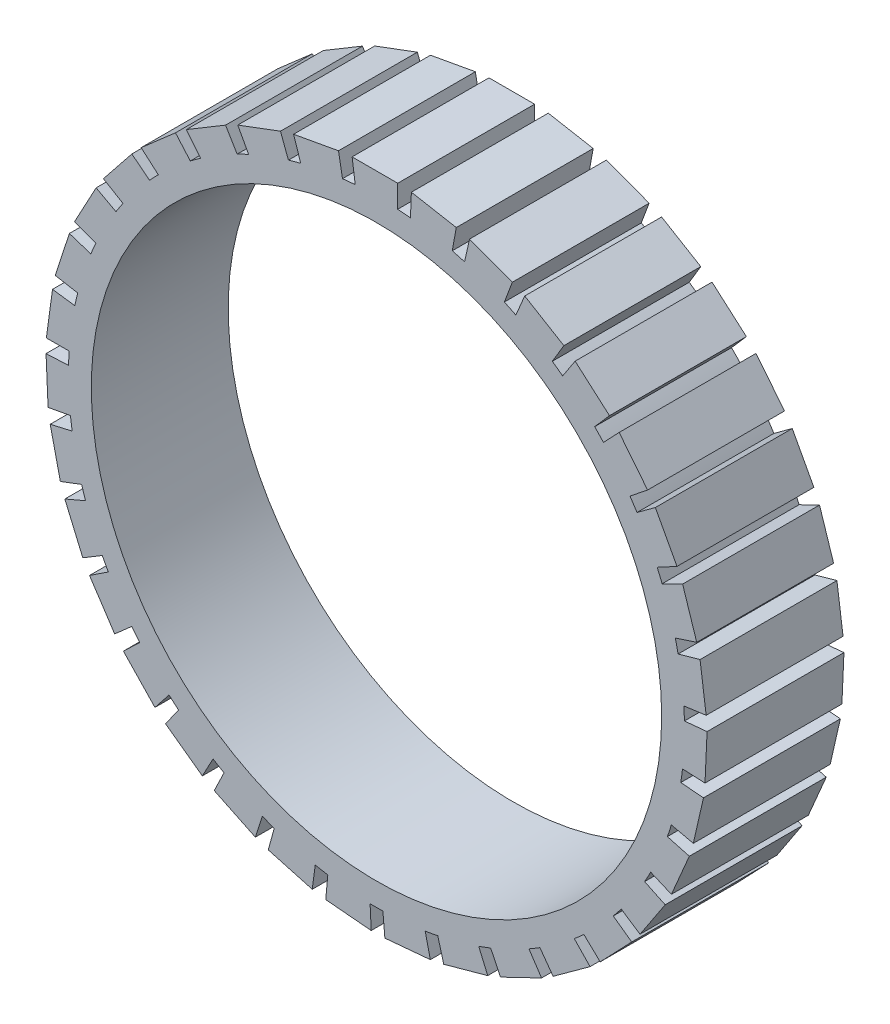
SolidWorks part; units mm, degrees
material "Rubber"
ref_plane "Front Plane" through (0, 0, 0) normal (0, 0, 1) x (1, 0, 0)
ref_plane "Top Plane" through (0, 0, 0) normal (0, 1, 0) x (1, 0, 0)
ref_plane "Right Plane" through (0, 0, 0) normal (1, 0, 0) x (0, 0, -1)
sketch "Sketch2" plane through (0, 0, 0) normal (0, 0, 1) x (1, 0, 0)
  line L1 (-2.1379, 28.9118) -> (1.8621, 28.9118)
  line L2 (-2.1379, 28.9118) -> (-1.8621, 26.9357)
  line L3 (1.8621, 28.9118) -> (1.8621, 26.9357)
  line L4 (3.0588, 28.8289) -> (6.9945, 28.1147)
  line L5 (3.0588, 28.8289) -> (2.9774, 26.8353)
  line L6 (6.9945, 28.1147) -> (6.6417, 26.1704)
  line L8 (8.1573, 27.8194) -> (11.9022, 26.4139)
  line L9 (8.1573, 27.8194) -> (7.7212, 25.8724)
  line L10 (11.9022, 26.4139) -> (11.2079, 24.5639)
  line L12 (12.9935, 25.9158) -> (16.4273, 23.8642)
  line L13 (12.9935, 25.9158) -> (12.2168, 24.078)
  line L14 (16.4273, 23.8642) -> (15.4138, 22.1679)
  line L16 (17.4122, 23.1793) -> (20.4245, 20.5475)
  line L17 (17.4122, 23.1793) -> (16.3198, 21.5096)
  line L18 (20.4245, 20.5475) -> (19.1243, 19.0594)
  line L20 (21.2712, 19.6977) -> (23.7651, 16.5704)
  line L21 (21.2712, 19.6977) -> (19.8982, 18.25)
  line L22 (23.7651, 16.5704) -> (22.2202, 15.3383)
  line L24 (24.4465, 15.583) -> (26.342, 12.0607)
  line L25 (24.4465, 15.583) -> (22.8371, 14.4037)
  line L26 (26.342, 12.0607) -> (24.6018, 11.1243)
  line L28 (26.8361, 10.9675) -> (28.0722, 7.1633)
  line L29 (26.8361, 10.9675) -> (25.042, 10.0945)
  line L30 (28.0722, 7.1633) -> (26.1928, 6.5527)
  line L32 (28.3631, 5.9995) -> (28.9001, 2.0357)
  line L33 (28.3631, 5.9995) -> (26.442, 5.4609)
  line L34 (28.9001, 2.0357) -> (26.9419, 1.7705)
  line L36 (28.9786, 0.8387) -> (28.7991, -3.1573)
  line L37 (28.9786, 0.8387) -> (26.9921, 0.6517)
  line L38 (28.7991, -3.1573) -> (26.8251, -3.0687)
  line L40 (28.6626, -4.3491) -> (27.7726, -8.2489)
  line L41 (28.6626, -4.3491) -> (26.6747, -4.1784)
  line L42 (27.7726, -8.2489) -> (25.846, -7.8091)
  line L43 (28.2729, -6.4531) -> (30.2228, -6.8981) construction
  line L44 (27.4255, -9.3972) -> (25.8534, -13.0753)
  line L45 (27.4255, -9.3972) -> (25.5, -8.8742)
  line L46 (25.8534, -13.0753) -> (24.0363, -12.2986)
  line L47 (26.6663, -11.3977) -> (28.5054, -12.1838) construction
  line L48 (25.3068, -14.1432) -> (23.1032, -17.4814)
  line L49 (25.3068, -14.1432) -> (23.5056, -13.2848)
  line L50 (23.1032, -17.4814) -> (21.454, -16.3928)
  line L51 (24.2026, -15.976) -> (25.8718, -17.0778) construction
  line L52 (22.3747, -18.4346) -> (19.6105, -21.3258)
  line L53 (22.3747, -18.4346) -> (20.7558, -17.2684)
  line L54 (19.6105, -21.3258) -> (18.1822, -19.9602)
  line L55 (20.9611, -20.0408) -> (22.4066, -21.4229) construction
  line L56 (18.7235, -22.1335) -> (15.4875, -24.4846)
  line L57 (18.7235, -22.1335) -> (17.3389, -20.697)
  line L58 (15.4875, -24.4846) -> (14.326, -22.8859)
  line L59 (17.0458, -23.4615) -> (18.2213, -25.0795) construction
  line L60 (14.4706, -25.121) -> (10.8667, -26.8565)
  line L61 (14.4706, -25.121) -> (13.3646, -23.4603)
  line L62 (10.8667, -26.8565) -> (10.0093, -25.0762)
  line L63 (12.5826, -26.1281) -> (13.4504, -27.93) construction
  line L64 (9.7525, -27.3011) -> (5.8966, -28.3653)
  line L65 (9.7525, -27.3011) -> (8.9609, -25.4696)
  line L66 (5.8966, -28.3653) -> (5.3709, -26.4604)
  line L67 (7.7151, -27.9549) -> (8.2471, -29.8828) construction
  line L68 (4.721, -28.6038) -> (0.7371, -28.9623)
  line L69 (4.721, -28.6038) -> (4.2691, -26.6604)
  line L70 (0.7371, -28.9623) -> (0.5599, -26.9942)
  line L71 (2.5995, -28.8833) -> (2.7788, -30.8752) construction
  line L72 (-0.4623, -28.987) -> (-4.4462, -28.6285)
  line L73 (-0.4623, -28.987) -> (-0.5599, -26.9942)
  line L74 (-4.4462, -28.6285) -> (-4.2691, -26.6604)
  line L75 (-2.5995, -28.8833) -> (-2.7788, -30.8752) construction
  line L76 (-5.6307, -28.4387) -> (-9.4866, -27.3745)
  line L77 (-5.6307, -28.4387) -> (-5.3709, -26.4604)
  line L78 (-9.4866, -27.3745) -> (-8.9609, -25.4696)
  line L79 (-7.7151, -27.9549) -> (-8.2471, -29.8828) construction
  line L80 (-10.6181, -26.9762) -> (-14.222, -25.2407)
  line L81 (-10.6181, -26.9762) -> (-10.0093, -25.0762)
  line L82 (-14.222, -25.2407) -> (-13.3646, -23.4603)
  line L83 (-12.5826, -26.1281) -> (-13.4504, -27.93) construction
  line L84 (-15.2643, -24.6468) -> (-18.5004, -22.2956)
  line L85 (-15.2643, -24.6468) -> (-14.326, -22.8859)
  line L86 (-18.5004, -22.2956) -> (-17.3389, -20.697)
  line L87 (-17.0458, -23.4615) -> (-18.2213, -25.0795) construction
  line L88 (-19.4198, -21.5251) -> (-22.1841, -18.634)
  line L89 (-19.4198, -21.5251) -> (-18.1822, -19.9602)
  line L90 (-22.1841, -18.634) -> (-20.7558, -17.2684)
  line L91 (-20.9611, -20.0408) -> (-22.4066, -21.4229) construction
  line L92 (-22.9512, -17.7117) -> (-25.1548, -14.3734)
  line L93 (-22.9512, -17.7117) -> (-21.454, -16.3928)
  line L94 (-25.1548, -14.3734) -> (-23.5056, -13.2848)
  line L95 (-24.2026, -15.976) -> (-25.8718, -17.0778) construction
  line L96 (-25.7449, -13.3289) -> (-27.317, -9.6508)
  line L97 (-25.7449, -13.3289) -> (-24.0363, -12.2986)
  line L98 (-27.317, -9.6508) -> (-25.5, -8.8742)
  line L99 (-26.6663, -11.3977) -> (-28.5054, -12.1838) construction
  line L100 (-27.7112, -8.5178) -> (-28.6013, -4.6181)
  line L101 (-27.7112, -8.5178) -> (-25.846, -7.8091)
  line L102 (-28.6013, -4.6181) -> (-26.6747, -4.1784)
  line L103 (-28.2729, -6.4531) -> (-30.2228, -6.8981) construction
  line L104 (-28.7868, -3.4329) -> (-28.9662, 0.5631)
  line L105 (-28.7868, -3.4329) -> (-26.8251, -3.0687)
  line L106 (-28.9662, 0.5631) -> (-26.9921, 0.6517)
  line L107 (-28.9708, -1.3011) -> (-30.9688, -1.3908) construction
  line L108 (-28.9371, 1.7623) -> (-28.4002, 5.7261)
  line L109 (-28.9371, 1.7623) -> (-26.9419, 1.7705)
  line L110 (-28.4002, 5.7261) -> (-26.442, 5.4609)
  line L111 (-28.7375, 3.8928) -> (-30.7194, 4.1612) construction
  line L112 (-28.1574, 6.9009) -> (-26.9213, 10.7052)
  line L113 (-28.1574, 6.9009) -> (-26.1928, 6.5527)
  line L114 (-26.9213, 10.7052) -> (-25.042, 10.0945)
  line L115 (-27.5806, 8.9615) -> (-29.4828, 9.5795) construction
  line L116 (-26.4727, 11.8177) -> (-24.5772, 15.3401)
  line L117 (-26.4727, 11.8177) -> (-24.6018, 11.1243)
  line L118 (-24.5772, 15.3401) -> (-22.8371, 14.4037)
  line L119 (-25.5373, 13.7422) -> (-27.2985, 14.6899) construction
  line L120 (-23.9371, 16.3547) -> (-21.4432, 19.482)
  line L121 (-23.9371, 16.3547) -> (-22.2202, 15.3383)
  line L122 (-21.4432, 19.482) -> (-19.8982, 18.25)
  line L123 (-22.6731, 18.0812) -> (-24.2368, 19.3282) construction
  line L124 (-20.6322, 20.366) -> (-17.6199, 22.9978)
  line L125 (-20.6322, 20.366) -> (-19.1243, 19.0594)
  line L126 (-17.6199, 22.9978) -> (-16.3198, 21.5096)
  line L128 (-16.6641, 23.7227) -> (-13.2303, 25.7743)
  line L129 (-16.6641, 23.7227) -> (-15.4138, 22.1679)
  line L130 (-13.2303, 25.7743) -> (-12.2168, 24.078)
  line L131 (-14.8741, 24.895) -> (-15.8999, 26.6119) construction
  line L132 (-12.1605, 26.317) -> (-8.4155, 27.7225)
  line L133 (-12.1605, 26.317) -> (-11.2079, 24.5639)
  line L134 (-8.4155, 27.7225) -> (-7.7212, 25.8724)
  line L135 (-10.1899, 27.1508) -> (-10.8926, 29.0233) construction
  line L136 (-7.266, 28.0654) -> (-3.3303, 28.7796)
  line L137 (-7.266, 28.0654) -> (-6.6417, 26.1704)
  line L138 (-3.3303, 28.7796) -> (-2.9774, 26.8353)
  line L139 (-5.1781, 28.534) -> (-5.5353, 30.5018) construction
  circle A0 centre (0, 0) radius 25
  circle A1 centre (0, 0) radius 29
  arc A2 (-1.8621, 26.9357) -> (-2.9774, 26.8353) centre (0, 0) ccw
  arc A38 (2.9774, 26.8353) -> (1.8621, 26.9357) centre (0, 0) ccw
  arc A39 (7.7212, 25.8724) -> (6.6417, 26.1704) centre (0, 0) ccw
  arc A40 (12.2168, 24.078) -> (11.2079, 24.5639) centre (0, 0) ccw
  arc A41 (16.3198, 21.5096) -> (15.4138, 22.1679) centre (0, 0) ccw
  arc A42 (19.8982, 18.25) -> (19.1243, 19.0594) centre (0, 0) ccw
  arc A43 (22.8371, 14.4037) -> (22.2202, 15.3383) centre (0, 0) ccw
  arc A44 (25.042, 10.0945) -> (24.6018, 11.1243) centre (0, 0) ccw
  arc A45 (26.442, 5.4609) -> (26.1928, 6.5527) centre (0, 0) ccw
  arc A46 (26.9921, 0.6517) -> (26.9419, 1.7705) centre (0, 0) ccw
  arc A47 (26.6747, -4.1784) -> (26.8251, -3.0687) centre (0, 0) ccw
  arc A48 (25.5, -8.8742) -> (25.846, -7.8091) centre (0, 0) ccw
  arc A49 (23.5056, -13.2848) -> (24.0363, -12.2986) centre (0, 0) ccw
  arc A50 (20.7558, -17.2684) -> (21.454, -16.3928) centre (0, 0) ccw
  arc A51 (17.3389, -20.697) -> (18.1822, -19.9602) centre (0, 0) ccw
  arc A52 (13.3646, -23.4603) -> (14.326, -22.8859) centre (0, 0) ccw
  arc A53 (8.9609, -25.4696) -> (10.0093, -25.0762) centre (0, 0) ccw
  arc A54 (4.2691, -26.6604) -> (5.3709, -26.4604) centre (0, 0) ccw
  arc A55 (-0.5599, -26.9942) -> (0.5599, -26.9942) centre (0, 0) ccw
  arc A56 (-5.3709, -26.4604) -> (-4.2691, -26.6604) centre (0, 0) ccw
  arc A57 (-10.0093, -25.0762) -> (-8.9609, -25.4696) centre (0, 0) ccw
  arc A58 (-14.326, -22.8859) -> (-13.3646, -23.4603) centre (0, 0) ccw
  arc A59 (-18.1822, -19.9602) -> (-17.3389, -20.697) centre (0, 0) ccw
  arc A60 (-21.454, -16.3928) -> (-20.7558, -17.2684) centre (0, 0) ccw
  arc A61 (-24.0363, -12.2986) -> (-23.5056, -13.2848) centre (0, 0) ccw
  arc A62 (-25.846, -7.8091) -> (-25.5, -8.8742) centre (0, 0) ccw
  arc A63 (-26.8251, -3.0687) -> (-26.6747, -4.1784) centre (0, 0) ccw
  arc A64 (-26.9419, 1.7705) -> (-26.9921, 0.6517) centre (0, 0) ccw
  arc A65 (-26.1928, 6.5527) -> (-26.442, 5.4609) centre (0, 0) ccw
  arc A66 (-24.6018, 11.1243) -> (-25.042, 10.0945) centre (0, 0) ccw
  arc A67 (-22.2202, 15.3383) -> (-22.8371, 14.4037) centre (0, 0) ccw
  arc A68 (-19.1243, 19.0594) -> (-19.8982, 18.25) centre (0, 0) ccw
  arc A69 (-15.4138, 22.1679) -> (-16.3198, 21.5096) centre (0, 0) ccw
  arc A70 (-11.2079, 24.5639) -> (-12.2168, 24.078) centre (0, 0) ccw
  arc A71 (-6.6417, 26.1704) -> (-7.7212, 25.8724) centre (0, 0) ccw
  point P10 (-0.1379, 28.9118)
  point P220 (0, 0)
  dimension "D1" = 50
  dimension "D3" = 54
  dimension "D4" = 4
  dimension "D2" = 4
  dimension "D5" = 35
extrude "Boss-Extrude1" add sketch "Sketch2" along normal blind 12 contours L137 A71 L134 A1 L133 A70 L130 L129 A69 L126 L125 A68 L122 L121 A67 L118 L117 A66 L114 L113 A65 L110 L109 A64 L106 L105 A63 L102 L101 A62 L98 L97
